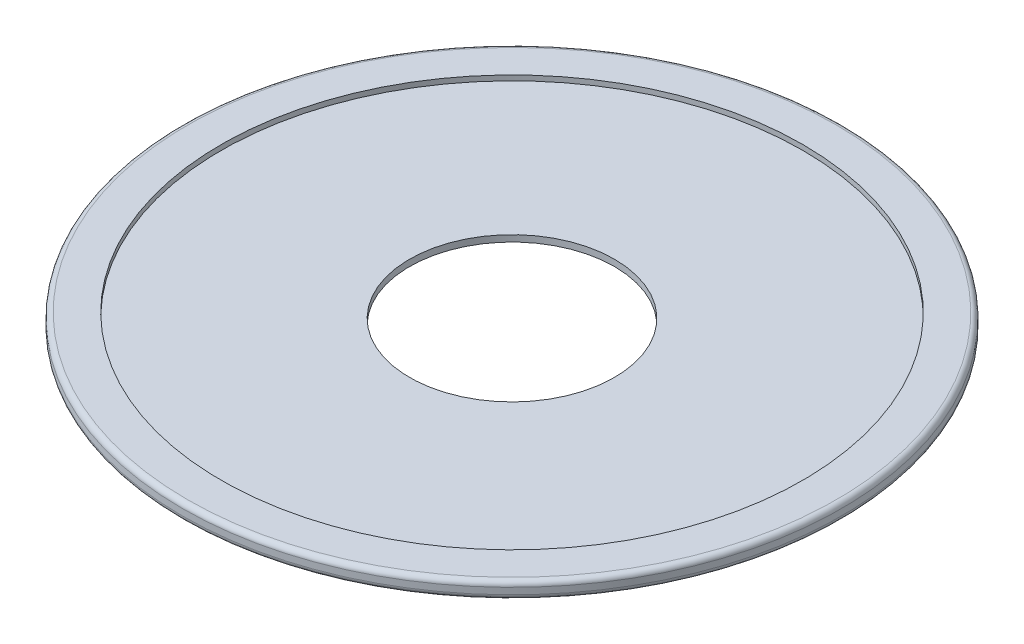
SolidWorks part; units mm, degrees
ref_plane "Front Plane" through (0, 0, 0) normal (0, 0, 1) x (1, 0, 0)
ref_plane "Top Plane" through (0, 0, 0) normal (0, 1, 0) x (1, 0, 0)
ref_plane "Right Plane" through (0, 0, 0) normal (1, 0, 0) x (0, 0, -1)
sketch "Sketch1" plane through (0, 0, 0) normal (0, 0, 1) x (1, 0, 0)
  line L0 (0, -187.0808) -> (0, 187.0808) construction
  line L2 (76.2, 0) -> (241.3, 0)
  line L3 (76.2, 0) -> (76.2, 4.7625)
  line L4 (76.2, 4.7625) -> (241.3, 4.7625)
  line L5 (241.3, 0) -> (241.3, 4.7625)
  point P4 (0, 0)
  dimension "D1" = 152.4
  dimension "D2" = 482.6
  dimension "D3" = 4.7625
revolve "Revolve1" add sketch "Sketch1" angle 360 about L0
sketch "Sketch2" plane through (0, 0, 0) normal (0, 0, 1) x (1, 0, 0)
  line L0 (216.3, -3.81) -> (241.3, -3.81)
  line L1 (245.11, 0) -> (245.11, 4.7625)
  line L2 (241.3, 8.5725) -> (216.3, 8.5725)
  line L3 (216.3, 8.5725) -> (216.3, 4.7625)
  line L4 (216.3, 4.7625) -> (241.3, 4.7625)
  line L5 (241.3, 4.7625) -> (241.3, 0)
  line L6 (241.3, 0) -> (216.3, 0)
  line L7 (216.3, 0) -> (216.3, -3.81)
  line L8 (0, 0) -> (0, 72.5208) construction
  arc A0 (241.3, -3.81) -> (245.11, 0) centre (241.3, 0) ccw
  arc A1 (245.11, 4.7625) -> (241.3, 8.5725) centre (241.3, 4.7625) ccw
  dimension "D1" = 12.3825
  dimension "D2" = 4.7625
  dimension "D3" = 28.81
revolve "Revolve2" add sketch "Sketch2" angle 360 about L8
